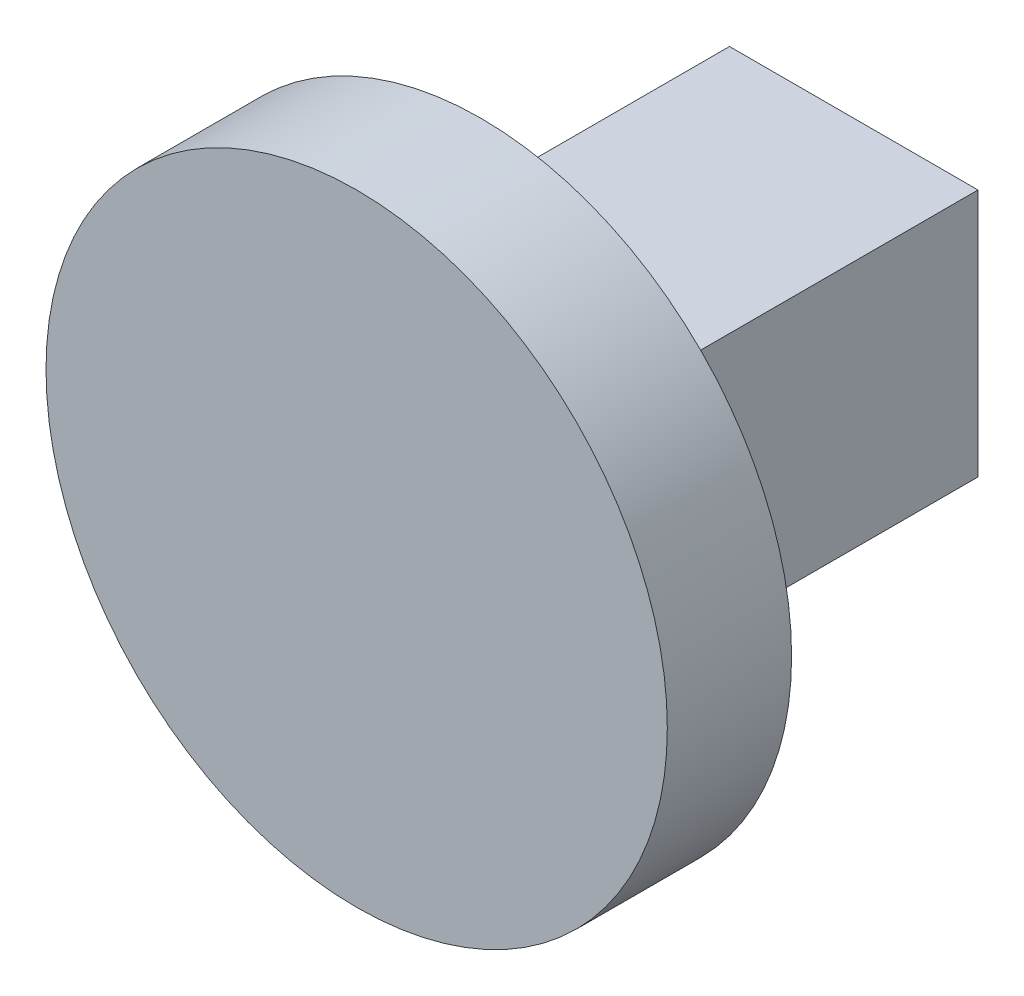
SolidWorks part; units mm, degrees
ref_plane "Alzado" through (0, 0, 0) normal (0, 0, 1) x (1, 0, 0)
ref_plane "Planta" through (0, 0, 0) normal (0, 1, 0) x (1, 0, 0)
ref_plane "Vista lateral" through (0, 0, 0) normal (1, 0, 0) x (0, 0, -1)
sketch "Croquis1" plane through (0, 0, 0) normal (0, 0, 1) x (1, 0, 0)
  line L1 (-5, -5) -> (5, -5)
  line L2 (-5, -5) -> (-5, 5)
  line L3 (-5, 5) -> (5, 5)
  line L4 (5, -5) -> (5, 5)
  line L5 (-5, -5) -> (5, 5) construction
  line L6 (-5, 5) -> (5, -5) construction
  point P0 (0, 0)
  dimension "D1" = 10
  dimension "D2" = 10
extrude "Saliente-Extruir1" add sketch "Croquis1" along normal blind 15
sketch "Croquis2" plane through (0, 0, 15) normal (0, 0, 1) x (1, 0, 0)
  circle A0 centre (0, 0) radius 12.5
  dimension "D1" = 25
extrude "Saliente-Extruir2" add sketch "Croquis2" along normal blind 5
